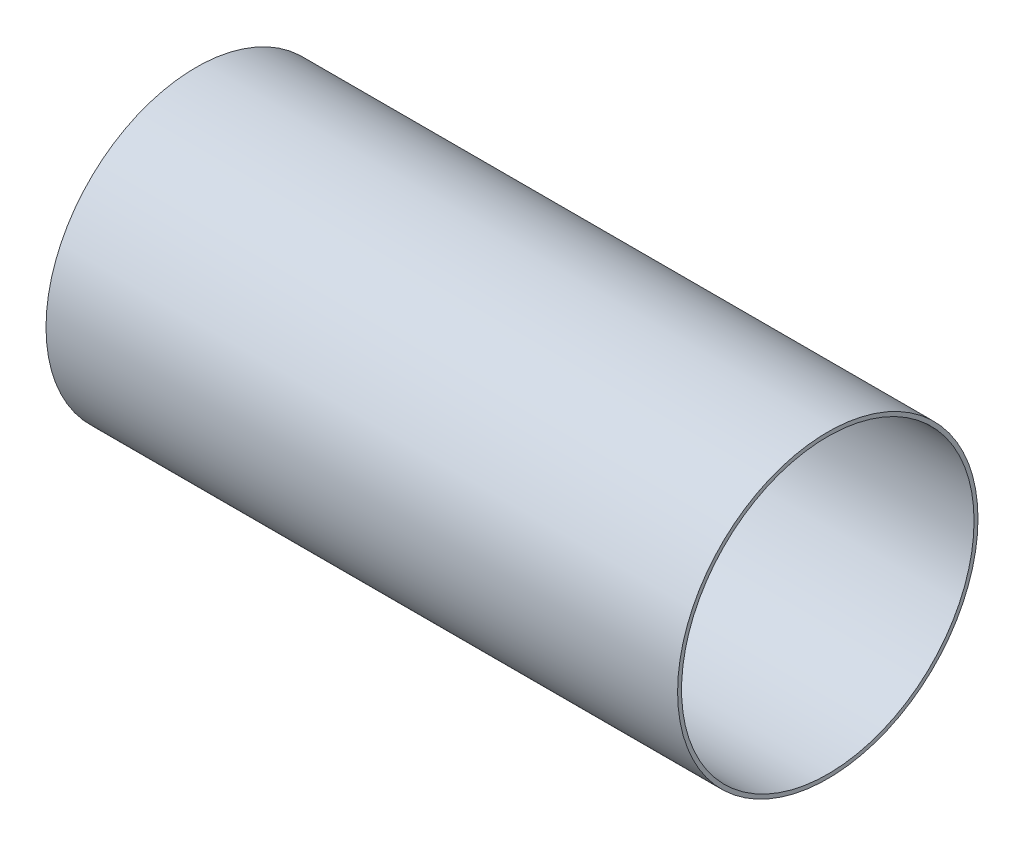
SolidWorks part; units mm, degrees
material "Thornel Mat VMA"
ref_plane "Front" through (0, 0, 0) normal (0, 0, 1) x (1, 0, 0)
ref_plane "Top" through (0, 0, 0) normal (0, 1, 0) x (1, 0, 0)
ref_plane "Right" through (0, 0, 0) normal (1, 0, 0) x (0, 0, -1)
sketch "Sketch1" plane through (0, 0, 0) normal (1, 0, 0) x (0, 0, -1)
  circle A0 centre (0, 0) radius 76.1
  circle A1 centre (0, 0) radius 74.1
  dimension "D1" = 152.2
  dimension "D2" = 148.2
extrude "Boss-Extrude1" add sketch "Sketch1" along normal blind 320
